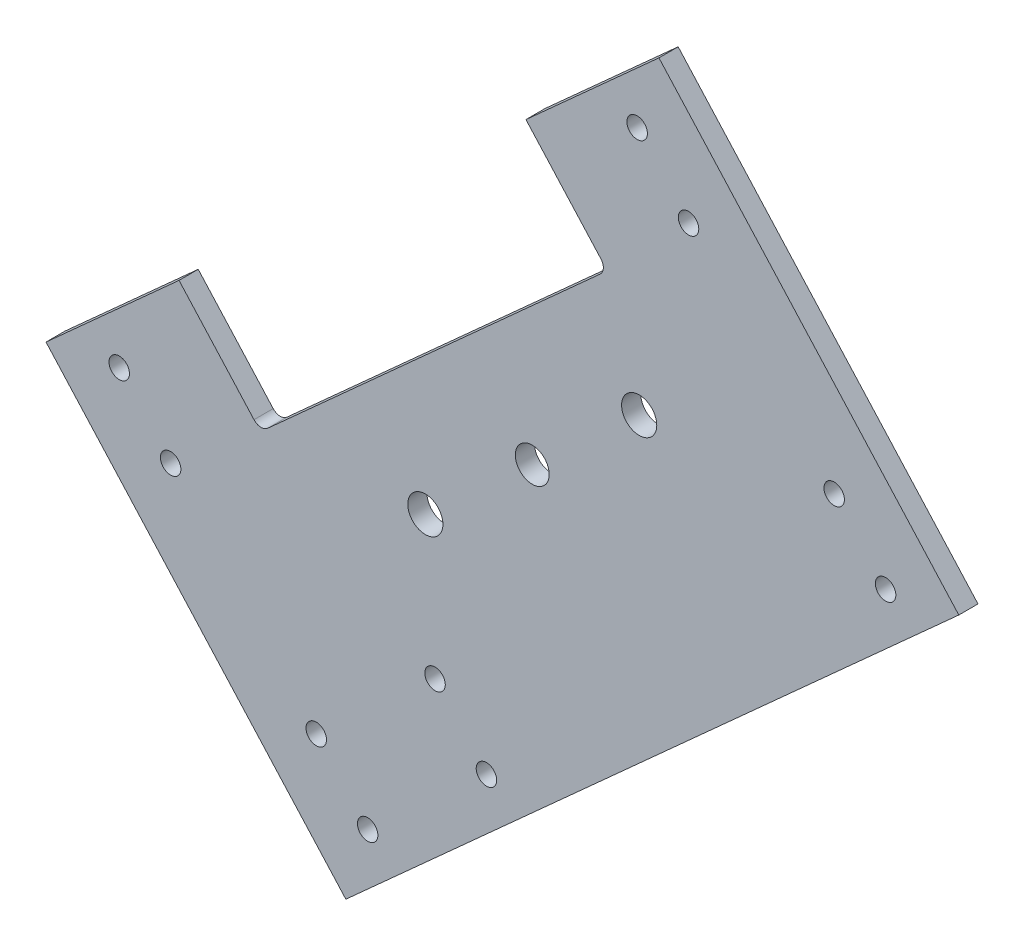
SolidWorks part; units mm, degrees
material "Thornel Mat VMA"
ref_plane "Front Plane" through (0, 0, 0) normal (0, 0, 1) x (1, 0, 0)
ref_plane "Top Plane" through (0, 0, 0) normal (0, 1, 0) x (1, 0, 0)
ref_plane "Right Plane" through (0, 0, 0) normal (1, 0, 0) x (0, 0, -1)
sketch "Sketch1" plane through (0, 0, 0) normal (0, 0, 1) x (1, 0, 0)
  line L0 (155.3058, -303.6576) -> (202.1772, -355.6488)
  line L1 (202.1772, -355.6488) -> (106.36, -442.0304)
  line L2 (106.36, -442.0304) -> (59.4887, -390.0392)
  line L3 (59.4887, -390.0392) -> (155.3058, -303.6576)
  line L4 (202.1772, -355.6488) -> (155.3058, -303.6576) construction
  line L5 (106.36, -442.0304) -> (59.4887, -390.0392) construction
  line L8 (59.4887, -390.0392) -> (61.7169, -388.0304) construction
  point P22 (0, 0)
  point P25 (0, 0)
  point P26 (0, 0)
  point P27 (0, 0)
  point P36 (165.4775, -241.6221)
  point P38 (173.5135, -250.534)
  point P40 (197.3537, -276.9727)
  point P42 (205.3897, -285.8846)
  point P44 (96.3945, -303.8907)
  point P46 (104.4296, -312.8035)
  point P48 (128.267, -339.2447)
  point P50 (136.3021, -348.1574)
  point P52 (116.3833, -349.9581)
  point P54 (124.4184, -358.8709)
  point P56 (84.5108, -314.6041)
  point P58 (92.5459, -323.5169)
  point P60 (0, 0)
  point P61 (0, 0)
  point P62 (0, 0)
  dimension "D1" = 70
extrude "Extrude1" add sketch "Sketch1" along normal blind 3
sketch "Sketch2" plane through (0, 0, 3) normal (0, 0, 1) x (1, 0, 0)
  line L0 (178.7415, -329.6532) -> (135.4997, -368.6368) construction
  line L1 (202.1772, -355.6488) -> (155.3058, -303.6576) construction
  circle A0 centre (135.4997, -368.6368) radius 2.65
  point P5 (135.3978, -368.4494)
  dimension "D1" = 5.3
  dimension "D2" = 58.22
extrude "Cut-Extrude1" cut sketch "Sketch2" against normal blind 5
sketch "Sketch4" plane through (0, 0, 3) normal (0, 0, 1) x (1, 0, 0)
  line L0 (80.2851, -371.2907) -> (134.5094, -322.4062)
  line L1 (80.2851, -371.2907) -> (92.003, -384.2885)
  line L2 (134.5094, -322.4062) -> (146.2272, -335.404)
  line L3 (94.1215, -384.3982) -> (146.1175, -337.5224)
  line L4 (155.3058, -303.6576) -> (59.4887, -390.0392) construction
  line L5 (59.4887, -390.0392) -> (106.36, -442.0304) construction
  line L6 (202.1772, -355.6488) -> (155.3058, -303.6576) construction
  circle A0 centre (151.8961, -314.8099) radius 1.6 construction
  circle A1 centre (159.9312, -323.7227) radius 1.6 construction
  circle A2 centre (182.6972, -348.9755) radius 1.6 construction
  circle A3 centre (190.7323, -357.8883) radius 1.6 construction
  circle A4 centre (70.9335, -387.7997) radius 1.6 construction
  circle A5 centre (78.9686, -396.7125) radius 1.6 construction
  circle A6 centre (120.303, -405.2255) radius 1.6 construction
  circle A7 centre (128.338, -414.1383) radius 1.6 construction
  circle A8 centre (101.7347, -421.9653) radius 1.6 construction
  circle A9 centre (109.7698, -430.8781) radius 1.6 construction
  circle A10 centre (151.8961, -314.8099) radius 1.6
  circle A11 centre (159.9312, -323.7227) radius 1.6
  circle A12 centre (182.6972, -348.9755) radius 1.6
  circle A13 centre (190.7323, -357.8883) radius 1.6
  circle A14 centre (70.9335, -387.7997) radius 1.6
  circle A15 centre (78.9686, -396.7125) radius 1.6
  circle A16 centre (120.303, -405.2255) radius 1.6
  circle A17 centre (128.338, -414.1383) radius 1.6
  circle A18 centre (101.7347, -421.9653) radius 1.6
  circle A19 centre (109.7698, -430.8781) radius 1.6
  arc A20 (154.2537, -351.7296) -> (150.1686, -355.4123) centre (152.2112, -353.571) ccw construction
  arc A21 (150.1686, -355.4123) -> (154.2537, -351.7296) centre (152.2112, -353.571) ccw construction
  arc A22 (120.8308, -381.8612) -> (116.7458, -385.5439) centre (118.7883, -383.7025) ccw construction
  arc A23 (116.7458, -385.5439) -> (120.8308, -381.8612) centre (118.7883, -383.7025) ccw construction
  arc A24 (154.2537, -351.7296) -> (150.1686, -355.4123) centre (152.2112, -353.571) ccw
  arc A25 (150.1686, -355.4123) -> (154.2537, -351.7296) centre (152.2112, -353.571) ccw
  arc A26 (120.8308, -381.8612) -> (116.7458, -385.5439) centre (118.7883, -383.7025) ccw
  arc A27 (116.7458, -385.5439) -> (120.8308, -381.8612) centre (118.7883, -383.7025) ccw
  arc A28 (92.003, -384.2885) -> (94.1215, -384.3982) centre (93.1171, -383.2841) ccw
  arc A29 (146.2272, -335.404) -> (146.1175, -337.5224) centre (145.1131, -336.4083) cw
  dimension "D4" = 1.5
  dimension "D1" = 28
  dimension "D2" = 28
  dimension "D3" = 19
extrude "Cut-Extrude3" cut sketch "Sketch4" against normal blind 3
